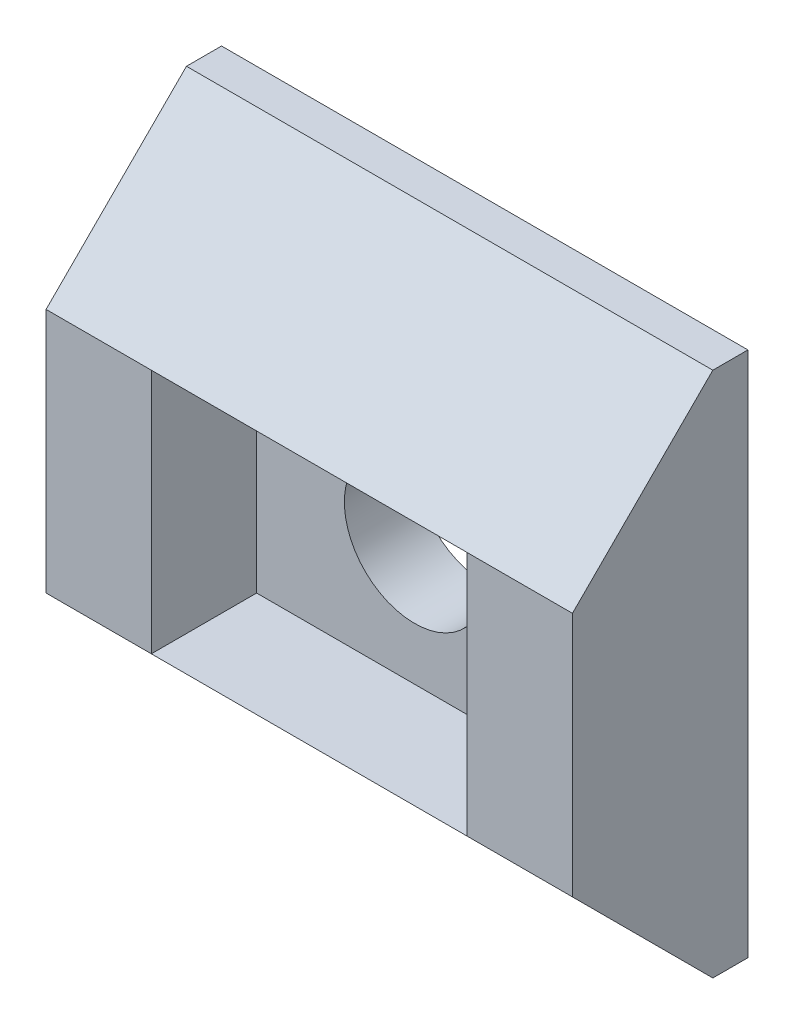
SolidWorks part; units mm, degrees
ref_plane "Front Plane" through (0, 0, 0) normal (0, 0, 1) x (1, 0, 0)
ref_plane "Top Plane" through (0, 0, 0) normal (0, 1, 0) x (1, 0, 0)
ref_plane "Right Plane" through (0, 0, 0) normal (1, 0, 0) x (0, 0, -1)
sketch "Sketch1" plane through (0, 0, 0) normal (0, 0, 1) x (1, 0, 0)
  line L1 (-7.5, -7.5) -> (7.5, -7.5)
  line L2 (-7.5, -7.5) -> (-7.5, 7.5)
  line L3 (-7.5, 7.5) -> (7.5, 7.5)
  line L4 (7.5, -7.5) -> (7.5, 7.5)
  line L5 (-7.5, -7.5) -> (7.5, 7.5) construction
  line L6 (-7.5, 7.5) -> (7.5, -7.5) construction
  point P0 (0, 0)
  dimension "D1" = 15
  dimension "D2" = 15
extrude "Boss-Extrude1" add sketch "Sketch1" along normal blind 5
sketch "Sketch2" plane through (-7.5, 0, 0) normal (-1, 0, 0) x (0, 0, 1)
  line L0 (1, 7.5) -> (5, 3.5)
  line L1 (5, 7.5) -> (0, 7.5) construction
  line L2 (5, 7.5) -> (5, -7.5) construction
  line L3 (1, -7.5) -> (5, -3.5)
  line L4 (5, -7.5) -> (0, -7.5) construction
  line L5 (0, 7.5) -> (0, -7.5) construction
  line L6 (1, 7.5) -> (5, 7.5)
  line L7 (5, 7.5) -> (5, 3.5)
  line L8 (1, -7.5) -> (5, -7.5)
  line L9 (5, -7.5) -> (5, -3.5)
  dimension "D1" = 1
  dimension "D2" = 1
  dimension "D3" = 4
  dimension "D4" = 4
extrude "Cut-Extrude1" cut sketch "Sketch2" against normal through all
sketch "Sketch3" plane through (0, 0, 5) normal (0, 0, 1) x (1, 0, 0)
  circle A0 centre (0, 0) radius 2
  dimension "D1" = 4
extrude "Cut-Extrude2" cut sketch "Sketch3" against normal through all
sketch "Sketch4" plane through (0, 0, 5) normal (0, 0, 1) x (1, 0, 0)
  line L1 (-4.5, 3.5) -> (4.5, 3.5)
  line L2 (-4.5, 3.5) -> (-4.5, -3.5)
  line L3 (-4.5, -3.5) -> (4.5, -3.5)
  line L4 (4.5, 3.5) -> (4.5, -3.5)
  line L5 (-4.5, 3.5) -> (4.5, -3.5) construction
  line L6 (-4.5, -3.5) -> (4.5, 3.5) construction
  point P0 (0, 0)
  dimension "D1" = 7
  dimension "D2" = 9
extrude "Cut-Extrude4" cut sketch "Sketch4" against normal blind 3
